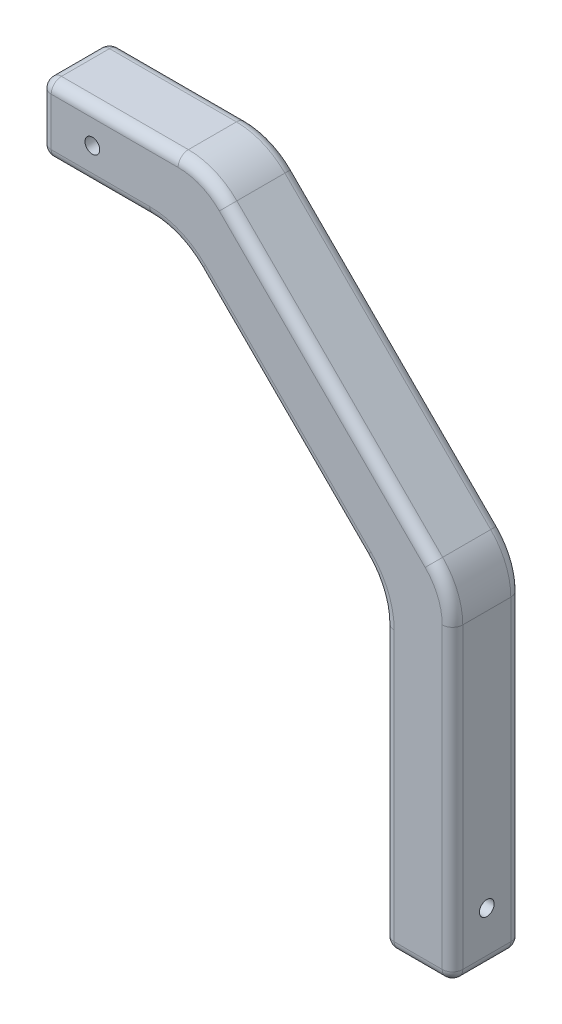
SolidWorks part; units mm, degrees
ref_plane "Alzado" through (0, 0, 0) normal (0, 0, 1) x (1, 0, 0)
ref_plane "Planta" through (0, 0, 0) normal (0, 1, 0) x (1, 0, 0)
ref_plane "Vista lateral" through (0, 0, 0) normal (1, 0, 0) x (0, 0, -1)
sketch "Croquis1" plane through (0, 0, 0) normal (0, 0, 1) x (1, 0, 0)
  line L0 (-60, 0) -> (60, 0) construction
  line L1 (-60, 0) -> (-11.7157, 0)
  line L2 (-11.7157, 0) -> (60, -71.7157)
  line L3 (60, -71.7157) -> (60, -170)
  line L4 (60, -170) -> (40, -170)
  line L5 (40, -170) -> (40, -80)
  line L6 (40, -80) -> (-20, -20)
  line L7 (-20, -20) -> (-60, -20)
  line L8 (-60, -20) -> (-60, 0)
  line L9 (60, -170) -> (60, -160) construction
  line L10 (-60, -10) -> (-45, -10) construction
  line L11 (50, -170) -> (50, -155) construction
  circle A0 centre (-45, -10) radius 2.15
  point P0 (-60, -10)
  point P4 (0, 0)
  dimension "D9" = 4.3
  dimension "D1" = 150
  dimension "D2" = 120
  dimension "D3" = 20
  dimension "D4" = 20
  dimension "D5" = 20
  dimension "D6" = 90
  dimension "D7" = 40
  dimension "D8" = 10
  dimension "D10" = 15
  dimension "D11" = 15
extrude "Saliente-Extruir1" add sketch "Croquis1" along normal blind 20
sketch "Croquis2" plane through (0, 0, 20) normal (0, 0, 1) x (1, 0, 0)
  line L0 (-60, -20) -> (-20, -20)
  line L1 (-20, -20) -> (-20, 0)
  line L2 (-60, 0) -> (-11.7157, 0) construction
  line L3 (-20, 0) -> (-60, 0)
  line L4 (-60, 0) -> (-60, -20)
extrude "Cortar-Extruir1" [suppressed] cut sketch "Croquis2" against normal blind 10
sketch "Croquis3" plane through (60, 0, 0) normal (1, 0, 0) x (0, 0, -1)
  line L0 (-20, -170) -> (0, -170)
  line L1 (0, -170) -> (0, -150)
  line L2 (0, -71.7157) -> (0, -170) construction
  line L3 (0, -150) -> (-20, -150)
  line L4 (-20, -71.7157) -> (-20, -170) construction
  line L5 (-20, -150) -> (-20, -170)
  dimension "D1" = 20
extrude "Cortar-Extruir2" [suppressed] cut sketch "Croquis3" against normal blind 10
fillet "Redondeo1" radius 20 4 edges at (40, -80, 10) (60, -71.7157, 10) (-20, -20, 10) (-11.7157, 0, 10)
sketch "Croquis4" plane through (40, 0, 0) normal (-1, 0, 0) x (0, 0, 1)
  line L0 (10, -170) -> (10, -155) construction
  line L1 (20, -170) -> (0, -170) construction
  circle A0 centre (10, -155) radius 2.15
  dimension "D2" = 4.3
  dimension "D1" = 15
extrude "Cortar-Extruir3" cut sketch "Croquis4" against normal blind 20
fillet "Redondeo2" radius 3 28 edges at (-40, 0, 20) (-12.3463, -1.5224, 20) (60, -125, 20) (58.4776, -72.3463, 20) (40, -129.1421, 20) (38.4776, -80.6306, 20) (-44.1421, -20, 20) (-20.6306, -21.5224, 20) (-40, 0, 0) (-12.3463, -1.5224, 0) (60, -125, 0) (58.4776, -72.3463, 0) (40, -129.1421, 0) (38.4776, -80.6306, 0) (-44.1421, -20, 0) (-20.6306, -21.5224, 0) (24.1421, -35.8579, 20) (10, -50, 20) (24.1421, -35.8579, 0) (10, -50, 0) (40, -170, 10) (50, -170, 0) (50, -170, 20) (60, -170, 10) (-60, -20, 10) (-60, -10, 0) (-60, -10, 20) (-60, 0, 10)
